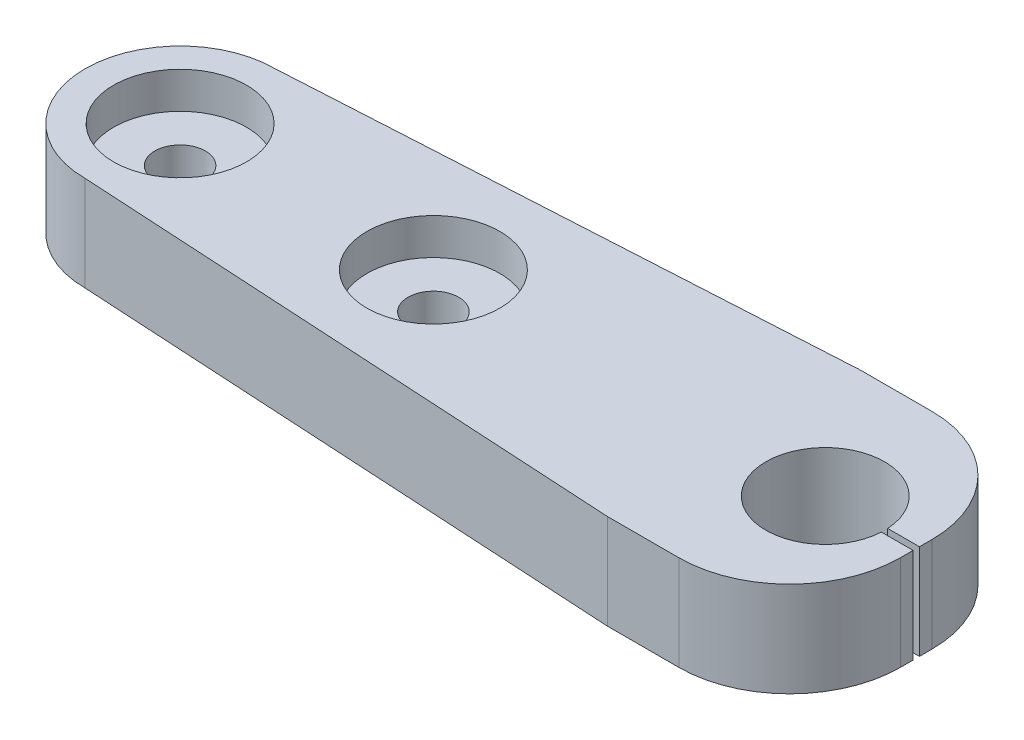
SolidWorks part; units mm, degrees
ref_plane "Piano frontale" through (0, 0, 0) normal (0, 0, 1) x (1, 0, 0)
ref_plane "Piano superiore" through (0, 0, 0) normal (0, 1, 0) x (1, 0, 0)
ref_plane "Piano destro" through (0, 0, 0) normal (1, 0, 0) x (0, 0, -1)
sketch "Sketch1" plane through (0, 0, 0) normal (0, 1, 0) x (1, 0, 0)
  line L18 (11.5, 10.2) -> (11.5, 11)
  line L20 (11.5, 9.8) -> (11.5, 9)
  line L23 (11.5, 10.2) -> (9.4947, 10.2)
  line L24 (11.5, 9.8) -> (9.4947, 9.8)
  line L25 (0, 18) -> (4.5, 18)
  line L26 (0, 2) -> (4.5, 2)
  line L27 (0, 2) -> (-35, 4)
  line L28 (0, 18) -> (-35, 16)
  circle A0 centre (-35, 10) radius 1.5
  circle A1 centre (-19, 10) radius 1.5
  arc A2 (-35, 16) -> (-35, 4) centre (-35, 10) ccw
  arc A3 (9.4947, 10.2) -> (9.4947, 9.8) centre (5.75, 10) ccw
  arc A4 (11.5, 11) -> (4.5, 18) centre (4.5, 11) ccw
  arc A5 (4.5, 2) -> (11.5, 9) centre (4.5, 9) ccw
  point P1 (-41, 10)
  dimension "D1" = 7
  dimension "D2" = 3.75
  dimension "D8" = 3
  dimension "D9" = 6
  dimension "D10" = 4.5
  dimension "D3" = 0.4
  dimension "D4" = 16
  dimension "D5" = 24.75
  dimension "D6" = 16
  dimension "D7" = 52.5
extrude "Boss-Extrude1" add sketch "Sketch1" along normal blind 6
hole_wizard "CBORE for M3 Hex Head Machine Screw1" positions "Sketch2" profile "Sketch3" counterbore size "M3" standard "ANSI Metric" end condition up to next
sketch "Sketch2" plane through (0, 6, 0) normal (0, 1, 0) x (1, 0, 0)
  point P0 (-19, 10)
  point P3 (-35, 10)
sketch "Sketch3" plane through (-19, 6, -10) normal (1, 0, 0) x (0, 0, 1)
  line L0 (0, 0) -> (0, 6)
  line L1 (0, 6) -> (1.6, 6)
  line L3 (1.6, 6) -> (1.6, 2.3)
  line L4 (1.6, 2.3) -> (4.2, 2.3)
  line L5 (4.2, 2.3) -> (4.2, 0)
  line L7 (4.2, 0) -> (0, 0)
  line L11 (0, -6.35) -> (0, 107.95) construction
  dimension "Thru Hole Dia." = 3.2
  dimension "Thru Hole Depth" = 6
  dimension "C'Bore Dia." = 8.4
  dimension "C'Bore Depth" = 2.3
